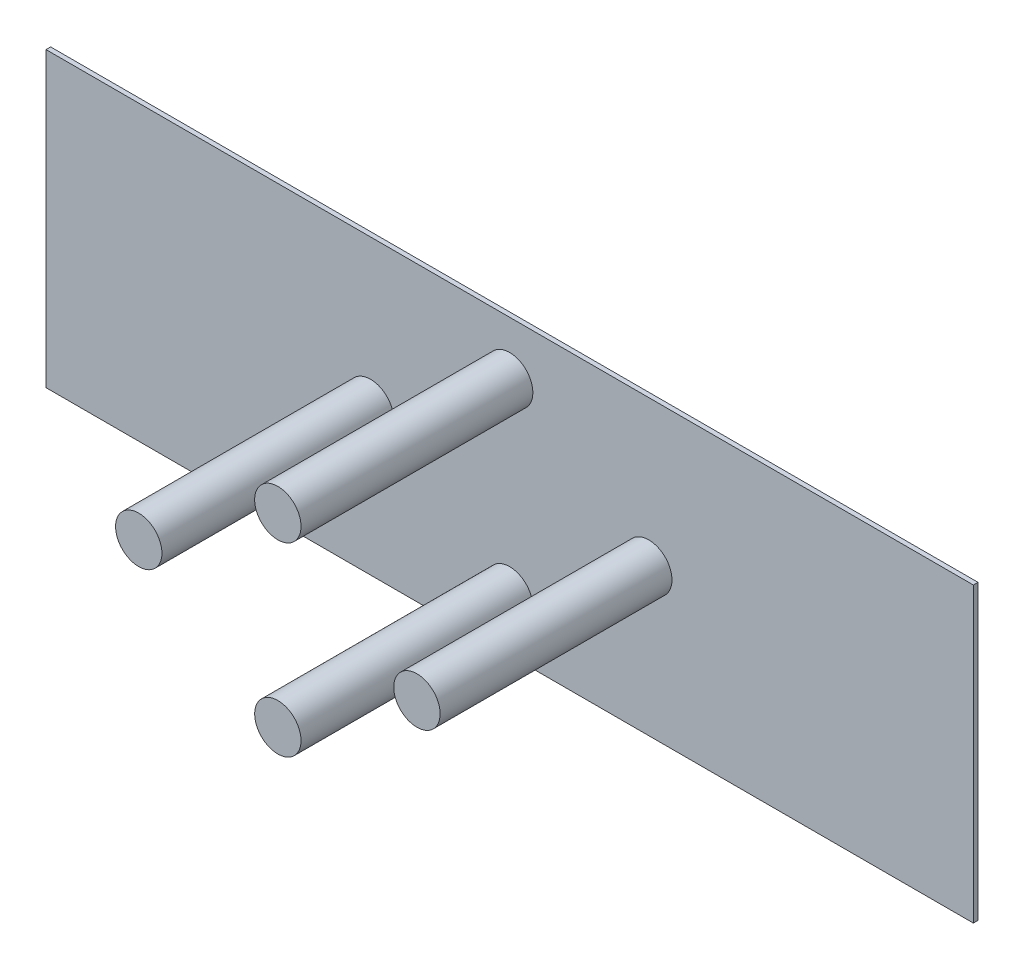
SolidWorks part; units mm, degrees
ref_plane "Front Plane" through (0, 0, 0) normal (0, 0, 1) x (1, 0, 0)
ref_plane "Top Plane" through (0, 0, 0) normal (0, 1, 0) x (1, 0, 0)
ref_plane "Right Plane" through (0, 0, 0) normal (1, 0, 0) x (0, 0, -1)
sketch "Sketch6" plane through (0, 0, 0) normal (0, 0, 1) x (1, 0, 0)
  line L1 (-5000, 3157.543) -> (15000, 3157.543)
  line L2 (-5000, 3157.543) -> (-5000, -3157.543)
  line L3 (-5000, -3157.543) -> (15000, -3157.543)
  line L4 (15000, 3157.543) -> (15000, -3157.543)
  line L5 (-5000, 3157.543) -> (15000, -3157.543) construction
  line L6 (-5000, -3157.543) -> (15000, 3157.543) construction
  point P0 (5000, 0)
  dimension "D1" = 5000
  dimension "D2" = 15000
extrude "Boss-Extrude3" add sketch "Sketch6" against normal blind 100
sketch "Sketch7" plane through (0, 0, 0) normal (0, 0, 1) x (1, 0, 0)
  line L0 (0, 0) -> (2000, 0) construction
  line L1 (0, 0) -> (8000, 0) construction
  circle A0 centre (2000, 0) radius 500
  circle A1 centre (8000, 0) radius 500
  circle A2 centre (5000, 2000) radius 500
  circle A3 centre (5000, -2000) radius 500
  dimension "D1" = 1000
  dimension "D2" = 1000
  dimension "D5" = 1000
  dimension "D3" = 2000
  dimension "D4" = 8000
  dimension "D6" = 2000
  dimension "D7" = 5000
extrude "Boss-Extrude4" add sketch "Sketch7" along normal blind 5000
